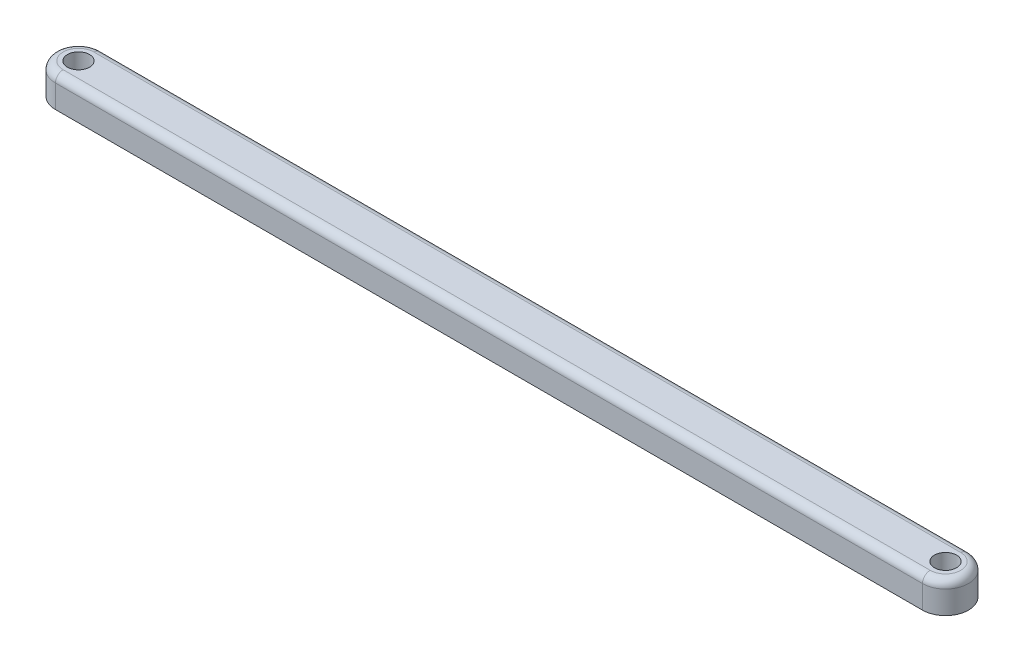
SolidWorks part; units mm, degrees
ref_plane "Front Plane" through (0, 0, 0) normal (0, 0, 1) x (1, 0, 0)
ref_plane "Top Plane" through (0, 0, 0) normal (0, 1, 0) x (1, 0, 0)
ref_plane "Right Plane" through (0, 0, 0) normal (1, 0, 0) x (0, 0, -1)
sketch "Sketch1" plane through (0, 0, 0) normal (0, 1, 0) x (1, 0, 0)
  line L0 (0, 0) -> (179.3875, 0) construction
  line L1 (0, 4.7625) -> (179.3875, 4.7625)
  line L2 (0, -4.7625) -> (179.3875, -4.7625)
  arc A0 (0, 4.7625) -> (0, -4.7625) centre (0, 0) ccw
  arc A1 (179.3875, -4.7625) -> (179.3875, 4.7625) centre (179.3875, 0) ccw
  point P3 (89.6938, 0)
  dimension "D1" = 179.3875
  dimension "D2" = 9.525
extrude "Boss-Extrude1" add sketch "Sketch1" along normal mid plane 6.35
sketch "Sketch2" plane through (0, 3.175, 0) normal (0, 1, 0) x (1, 0, 0)
  circle A0 centre (0, 0) radius 2.286
  circle A1 centre (179.3875, 0) radius 2.286
  dimension "D1" = 4.572
extrude "Cut-Extrude1" cut sketch "Sketch2" against normal through all
fillet "Fillet1" radius 1.5875 4 edges at (184.15, 3.175, 0) (89.6938, 3.175, 4.7625) (-4.7625, 3.175, 0) (89.6938, 3.175, -4.7625)
